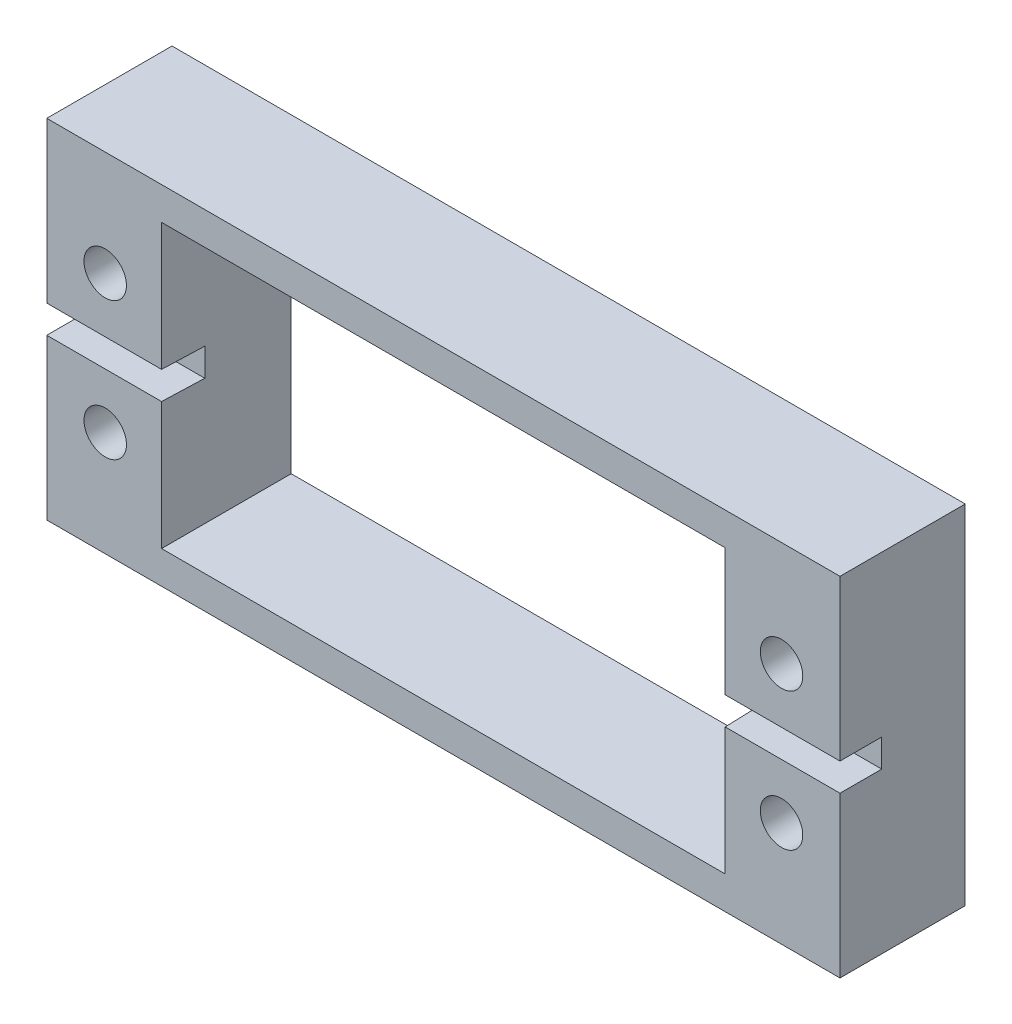
SolidWorks part; units mm, degrees
ref_plane "前视基准面" through (0, 0, 0) normal (0, 0, 1) x (1, 0, 0)
ref_plane "上视基准面" through (0, 0, 0) normal (0, 1, 0) x (1, 0, 0)
ref_plane "右视基准面" through (0, 0, 0) normal (1, 0, 0) x (0, 0, -1)
sketch "草图1" plane through (0, 0, 0) normal (0, 0, 1) x (1, 0, 0)
  line L0 (0, 0) -> (31.2771, 0) construction
  line L1 (0, 0) -> (0, 9.6949) construction
  line L7 (-20.5, -10.3) -> (20.5, 10.3) construction
  line L8 (-20.5, 10.3) -> (20.5, -10.3) construction
  line L9 (-28.5, -12.5) -> (28.5, -12.5)
  line L10 (-28.5, -12.5) -> (-28.5, 12.5)
  line L11 (-28.5, 12.5) -> (28.5, 12.5)
  line L12 (28.5, -12.5) -> (28.5, 12.5)
  line L13 (-28.5, -12.5) -> (28.5, 12.5) construction
  line L14 (-28.5, 12.5) -> (28.5, -12.5) construction
  circle A0 centre (24.3, 4.95) radius 1.525
  circle A1 centre (-24.3, 4.95) radius 1.525
  circle A2 centre (-24.3, -4.95) radius 1.525
  circle A3 centre (24.3, -4.95) radius 1.525
  dimension "D1" = 3.05
  dimension "D2" = 24.3
  dimension "D3" = 4.95
  dimension "D6" = 57
  dimension "D7" = 25
extrude "凸台-拉伸1" add sketch "草图1" along normal blind 9
sketch "草图2" plane through (0, 0, 9) normal (0, 0, 1) x (1, 0, 0)
  line L0 (28.5, -12.5) -> (28.5, 12.5) construction
  line L1 (-28.5, -1) -> (28.5, -1)
  line L2 (-28.5, -1) -> (-28.5, 1)
  line L3 (-28.5, 1) -> (28.5, 1)
  line L4 (28.5, -1) -> (28.5, 1)
  line L5 (-28.5, -1) -> (28.5, 1) construction
  line L6 (-28.5, 1) -> (28.5, -1) construction
  point P0 (0, 0)
  dimension "D1" = 2
extrude "切除-拉伸1" cut sketch "草图2" against normal blind 3
sketch "草图3" plane through (0, 0, 9) normal (0, 0, 1) x (1, 0, 0)
  line L1 (-20.25, -10.15) -> (20.25, -10.15)
  line L2 (-20.25, -10.15) -> (-20.25, 10.15)
  line L3 (-20.25, 10.15) -> (20.25, 10.15)
  line L4 (20.25, -10.15) -> (20.25, 10.15)
  line L5 (-20.25, -10.15) -> (20.25, 10.15) construction
  line L6 (-20.25, 10.15) -> (20.25, -10.15) construction
  point P0 (0, 0)
  dimension "D1" = 40.5
  dimension "D2" = 20.3
extrude "切除-拉伸2" cut sketch "草图3" against normal blind 15 draft 2
